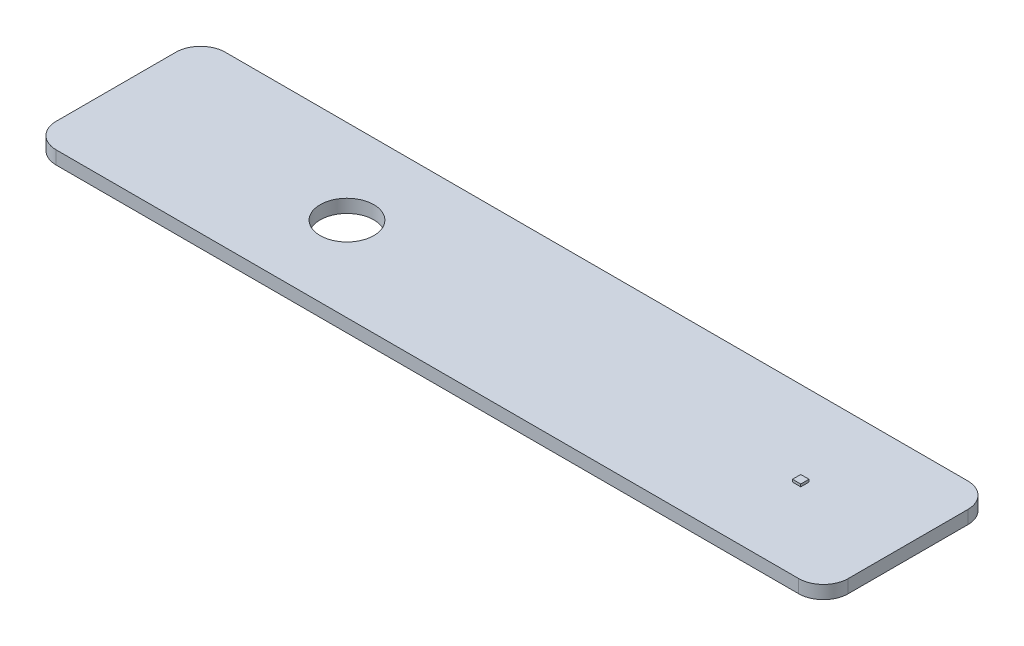
SolidWorks part; units mm, degrees
material "Custom Plastic"
ref_plane "Front Plane" through (0, 0, 0) normal (0, 0, 1) x (1, 0, 0)
ref_plane "Top Plane" through (0, 0, 0) normal (0, 1, 0) x (1, 0, 0)
ref_plane "Right Plane" through (0, 0, 0) normal (1, 0, 0) x (0, 0, -1)
sketch "Sketch1" plane through (0, 0, 0) normal (0, 1, 0) x (1, 0, 0)
  line L1 (-45, 10.25) -> (45, 10.25)
  line L2 (-48, 7.25) -> (-48, -7.25)
  line L3 (-45, -10.25) -> (45, -10.25)
  line L4 (48, 7.25) -> (48, -7.25)
  line L5 (-48, 10.25) -> (48, -10.25) construction
  line L6 (-48, -10.25) -> (48, 10.25) construction
  arc A0 (-48, -7.25) -> (-45, -10.25) centre (-45, -7.25) ccw
  arc A1 (45, -10.25) -> (48, -7.25) centre (45, -7.25) ccw
  arc A2 (45, 10.25) -> (48, 7.25) centre (45, 7.25) cw
  arc A3 (-45, 10.25) -> (-48, 7.25) centre (-45, 7.25) ccw
  point P0 (0, 0)
  dimension "D3" = 3
  dimension "D1" = 96
  dimension "D2" = 20.5
extrude "Boss-Extrude1" add sketch "Sketch1" along normal blind 1.6 contours L3 A1 L4 A2 L1 A3 L2 A0
sketch "Sketch2" plane through (0, 1.6, 0) normal (0, 1, 0) x (1, 0, 0)
  line L1 (34.5, 0.5) -> (35.5, 0.5)
  line L2 (34.5, 0.5) -> (34.5, -0.5)
  line L3 (34.5, -0.5) -> (35.5, -0.5)
  line L4 (35.5, 0.5) -> (35.5, -0.5)
  line L5 (34.5, 0.5) -> (35.5, -0.5) construction
  line L6 (34.5, -0.5) -> (35.5, 0.5) construction
  line L7 (-48, 0) -> (48, 0) construction
  line L8 (-48, 7.25) -> (-48, -7.25) construction
  line L9 (48, 7.25) -> (48, -7.25) construction
  point P0 (35, 0)
  dimension "D1" = 1
  dimension "D2" = 1
  dimension "D3" = 83
extrude "Boss-Extrude2" add sketch "Sketch2" along normal blind 0.3 contours L3 L4 L1 L2
sketch "Sketch3" plane through (0, 1.6, 0) normal (0, 1, 0) x (1, 0, 0)
  line L0 (-48, 7.25) -> (-48, -7.25) construction
  line L1 (-45, -10.25) -> (45, -10.25) construction
  circle A0 centre (-20, 0) radius 3.25
  dimension "D1" = 6.5
  dimension "D2" = 28
  dimension "D3" = 10.25
extrude "Cut-Extrude1" cut sketch "Sketch3" against normal through all
